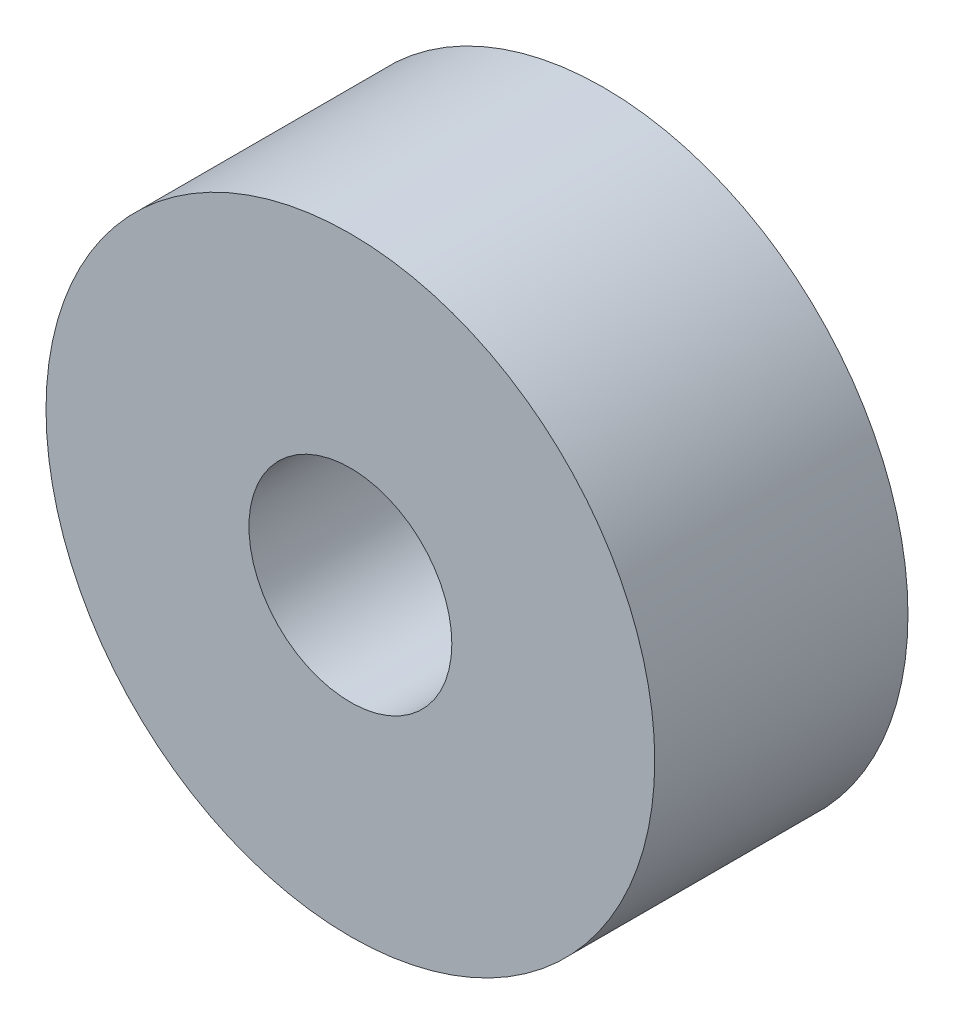
SolidWorks part; units mm, degrees
ref_plane "Front Plane" through (0, 0, 0) normal (0, 0, 1) x (1, 0, 0)
ref_plane "Top Plane" through (0, 0, 0) normal (0, 1, 0) x (1, 0, 0)
ref_plane "Right Plane" through (0, 0, 0) normal (1, 0, 0) x (0, 0, -1)
sketch "Sketch1" plane through (0, 0, 0) normal (0, 0, 1) x (1, 0, 0)
  circle A0 centre (0, 0) radius 1.5875
  circle A1 centre (0, 0) radius 4.7625
extrude "Boss-Extrude1" add sketch "Sketch1" along normal blind 3.9624
